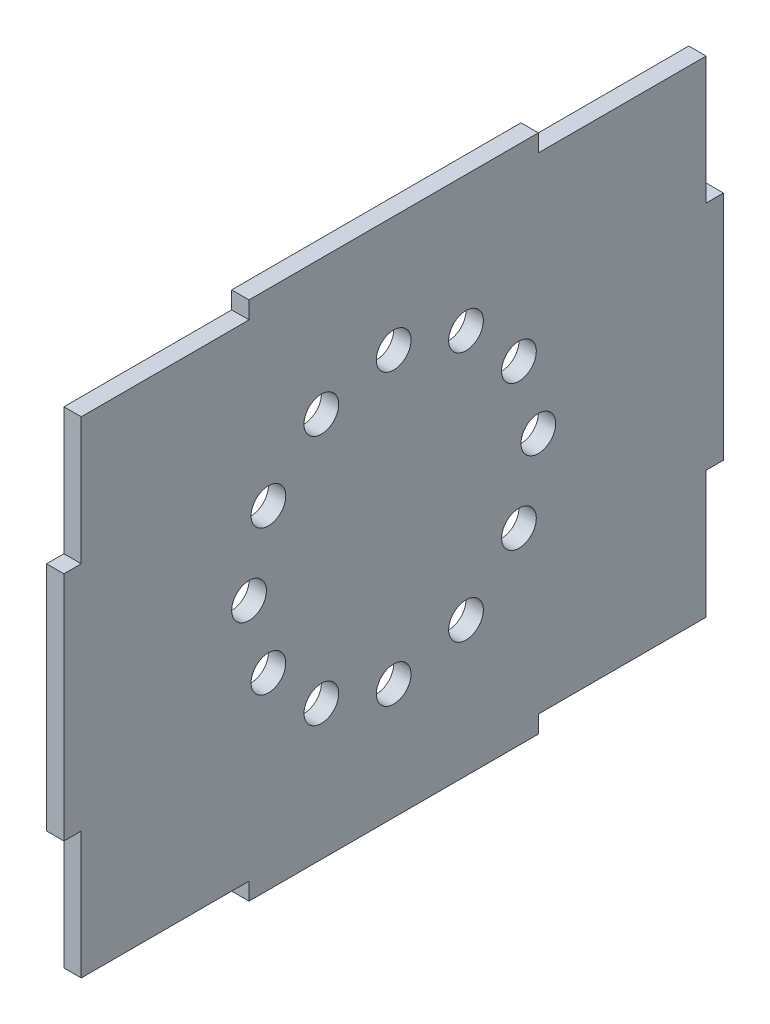
SolidWorks part; units mm, degrees
ref_plane "Спереди" through (0, 0, 0) normal (0, 0, 1) x (1, 0, 0)
ref_plane "Сверху" through (0, 0, 0) normal (0, 1, 0) x (1, 0, 0)
ref_plane "Справа" through (0, 0, 0) normal (1, 0, 0) x (0, 0, -1)
other "Configuration Table"
sketch "Эскиз1" plane through (0, 0, 0) normal (1, 0, 0) x (0, 0, -1)
  line L0 (57, 90) -> (57, 0) construction
  line L1 (0, 0) -> (114, 0) construction
  line L2 (0, 0) -> (0, 90) construction
  line L3 (0, 90) -> (114, 90) construction
  line L4 (114, 0) -> (114, 90) construction
  line L5 (0, 45) -> (114, 45) construction
  line L6 (0, 65) -> (0, 25)
  line L7 (0, 25) -> (3, 25)
  line L8 (3, 25) -> (3, 3)
  line L9 (3, 3) -> (32, 3)
  line L10 (32, 3) -> (32, 0)
  line L11 (32, 0) -> (82, 0)
  line L12 (82, 3) -> (82, 0)
  line L13 (111, 3) -> (82, 3)
  line L14 (111, 25) -> (111, 3)
  line L15 (114, 25) -> (111, 25)
  line L16 (114, 65) -> (114, 25)
  line L17 (0, 90) -> (114, 90) construction
  line L18 (114, 65) -> (111, 65)
  line L19 (111, 65) -> (111, 87)
  line L20 (111, 87) -> (82, 87)
  line L21 (82, 87) -> (82, 90)
  line L22 (32, 90) -> (82, 90)
  line L23 (32, 87) -> (32, 90)
  line L24 (3, 87) -> (32, 87)
  line L25 (3, 65) -> (3, 87)
  line L26 (0, 65) -> (3, 65)
  point P29 (32, 1.5)
  dimension "D1" = 25
  dimension "D2" = 90
  dimension "D3" = 40
  dimension "D4" = 32
  dimension "D5" = 114
  dimension "D6" = 50
  dimension "D7" = 3
  dimension "D8" = 3
extrude "Бобышка-Вытянуть1" add sketch "Эскиз1" along normal blind 3
sketch "Эскиз2" plane through (3, 0, 0) normal (1, 0, 0) x (0, 0, -1)
  line L0 (57, 90) -> (57, 0) construction
  line L1 (82, 90) -> (32, 90) construction
  line L2 (32, 0) -> (82, 0) construction
  line L3 (0, 45) -> (114, 45) construction
  line L4 (0, 65) -> (0, 25) construction
  line L5 (114, 25) -> (114, 65) construction
  circle A0 centre (57, 45) radius 25 construction
  circle A1 centre (32, 45) radius 3
  circle A2 centre (35.3494, 57.5) radius 3
  circle A3 centre (44.5, 66.6506) radius 3
  circle A4 centre (57, 70) radius 3
  circle A5 centre (69.5, 66.6506) radius 3
  circle A6 centre (78.6506, 57.5) radius 3
  circle A7 centre (82, 45) radius 3
  circle A8 centre (78.6506, 32.5) radius 3
  circle A9 centre (69.5, 23.3494) radius 3
  circle A10 centre (57, 20) radius 3
  circle A11 centre (44.5, 23.3494) radius 3
  circle A12 centre (35.3494, 32.5) radius 3
  point P41 (57, 45)
  dimension "D1" = 50
  dimension "D2" = 12
extrude "Вырез-Вытянуть1" cut sketch "Эскиз2" against normal through all
